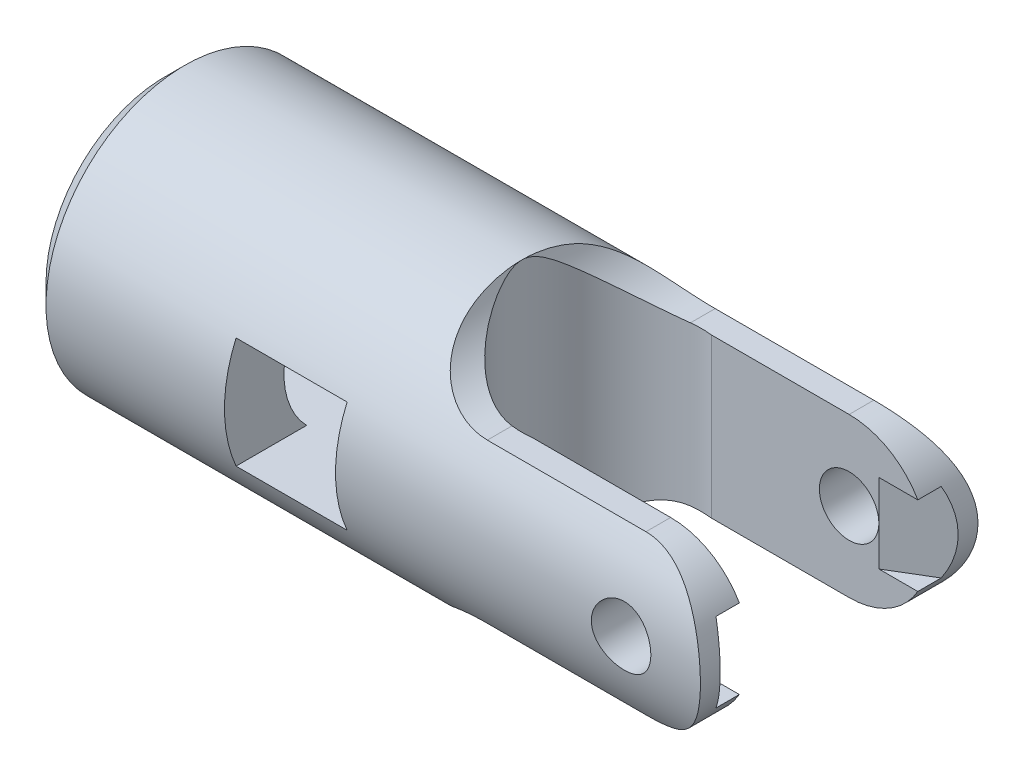
SolidWorks part; units mm, degrees
ref_plane "前视基准面" through (0, 0, 0) normal (0, 0, 1) x (1, 0, 0)
ref_plane "上视基准面" through (0, 0, 0) normal (0, 1, 0) x (1, 0, 0)
ref_plane "右视基准面" through (0, 0, 0) normal (1, 0, 0) x (0, 0, -1)
sketch "草图1" plane through (0, 0, 0) normal (1, 0, 0) x (0, 0, -1)
  circle A0 centre (0, 0) radius 3.5
  dimension "D1" = 7
extrude "凸台-拉伸1" add sketch "草图1" along normal blind 17
sketch "草图2" plane through (17, 0, 0) normal (1, 0, 0) x (0, 0, -1)
  line L0 (-3.5, 0) -> (3.5, 0) construction
  line L1 (-2.8723, -2) -> (-2.25, -2)
  line L2 (-2.8723, 2) -> (-2.25, 2)
  line L3 (0, 2) -> (0, -2) construction
  line L4 (-3.5, 2) -> (3.5, 2) construction
  line L5 (-3.5, -2) -> (3.5, -2) construction
  line L6 (-2.25, 2) -> (-2.25, -2)
  line L7 (2.25, 2) -> (2.25, -2)
  line L8 (2.25, 2) -> (2.8723, 2)
  line L9 (2.25, -2) -> (2.8723, -2)
  circle A0 centre (0, 0) radius 3.5 construction
  arc A1 (-2.8723, -2) -> (2.8723, -2) centre (0, 0) ccw
  arc A2 (2.8723, 2) -> (-2.8723, 2) centre (0, 0) ccw
  dimension "D3" = 7
  dimension "D1" = 2
  dimension "D2" = 2
  dimension "D4" = 2.25
  dimension "D5" = 2.25
extrude "切除-拉伸2" cut sketch "草图2" against normal blind 6
sketch "草图3" plane through (0, 0, 0) normal (0, 0, 1) x (1, 0, 0)
  line L0 (17, 0) -> (15, 0) construction
  line L1 (17, -2) -> (17, 2) construction
  line L2 (15, 2) -> (17, 2)
  line L3 (17, 2) -> (17, 0)
  arc A0 (17, 0) -> (15, 2) centre (15, 0) ccw
  dimension "D1" = 2
  dimension "D2" = 2
extrude "切除-拉伸3" cut sketch "草图3" against normal up to next and the other way up to next
mirror "镜向1" about plane through (0, 0, 0) normal (0, 1, 0) of "切除-拉伸3"
sketch "草图4" plane through (0, 0, 0) normal (0, 0, 1) x (1, 0, 0)
  line L0 (17, 0) -> (15, 0) construction
  arc A0 (15, -2) -> (15, 2) centre (15, 0) ccw construction
  circle A1 centre (15, 0) radius 0.75
  dimension "D1" = 1.5
extrude "切除-拉伸4" cut sketch "草图4" against normal up to next and the other way up to next
sketch "草图5" plane through (0, 0, 0) normal (0, 1, 0) x (1, 0, 0)
  line L0 (11, 0) -> (9, 0) construction
  line L1 (11, -2.8723) -> (11, 2.8723) construction
  circle A0 centre (11.2656, 0) radius 2.2656
  dimension "D1" = 2
extrude "切除-拉伸5" cut sketch "草图5" against normal up to next and the other way up to next
sketch "草图6" plane through (0, 0, 0) normal (0, 0, 1) x (1, 0, 0)
  circle A0 centre (11, 4.0833) radius 2.0833
extrude "切除-拉伸6" cut sketch "草图6" against normal up to next and the other way up to next
mirror "镜向2" about plane through (0, 0, 0) normal (0, 1, 0) of "切除-拉伸6"
sketch "草图7" plane through (0, 0, 0) normal (0, 0, 1) x (1, 0, 0)
  line L0 (0, 0) -> (6.4, 0) construction
  line L1 (5, 1.4) -> (5, -1.4)
  line L2 (5, 1.4) -> (7.8, 1.4)
  line L3 (5, -1.4) -> (7.8, -1.4)
  line L4 (7.8, 1.4) -> (7.8, -1.4)
  line L5 (5, 1.4) -> (7.8, -1.4) construction
  line L6 (5, -1.4) -> (7.8, 1.4) construction
  dimension "D1" = 6.4
  dimension "D2" = 2.8
  dimension "D3" = 2.8
extrude "切除-拉伸7" cut sketch "草图7" against normal up to next and the other way up to next
sketch "草图8" plane through (0, 0, 0) normal (-1, 0, 0) x (0, 0, 1)
  line L0 (-2, 0) -> (2, 0) construction
  line L1 (-1.4283, -1.4) -> (1.4283, -1.4)
  line L2 (-1.4283, 1.4) -> (1.4283, 1.4)
  line L4 (-2, 1.4) -> (2, 1.4) construction
  line L5 (-2, -1.4) -> (2, -1.4) construction
  arc A0 (1.4283, -1.4) -> (1.4283, 1.4) centre (0, 0) ccw
  arc A1 (-1.4283, 1.4) -> (-1.4283, -1.4) centre (0, 0) ccw
  dimension "D1" = 4
  dimension "D2" = 1.4
  dimension "D3" = 1.4
extrude "切除-拉伸8" cut sketch "草图8" against normal up to next
chamfer "倒角1" distance 0.5 angle 45 5 edges at (0, 0, -3.5) (0, 0, 2) (0, 1.4, 0) (0, 0, -2) (0, -1.4, 0)
sketch "草图9" plane through (0, 0, 0) normal (0, 1, 0) x (1, 0, 0)
  line L0 (17, 2.25) -> (15.75, 2.25)
  line L1 (15.75, 2.25) -> (17, 3)
  line L2 (17, 2.25) -> (17, 3.5) construction
  line L3 (17, 3) -> (17, 2.25)
  dimension "D1" = 1.25
  dimension "D2" = 0.75
extrude "切除-拉伸9" cut sketch "草图9" against normal blind 1 and the other way blind 1
mirror "镜向3" about plane through (0, 0, 0) normal (0, 0, 1) of "切除-拉伸9"
